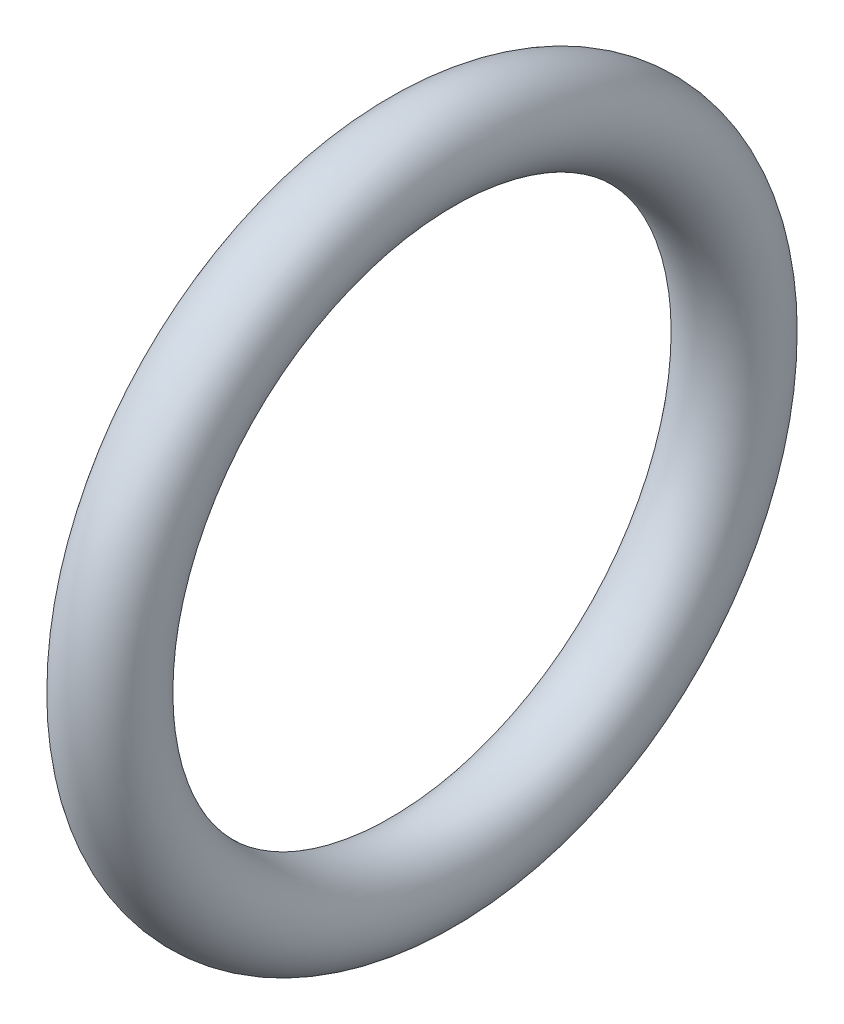
SolidWorks part; units mm, degrees
ref_plane "前视基准面" through (0, 0, 0) normal (0, 0, 1) x (1, 0, 0)
ref_plane "上视基准面" through (0, 0, 0) normal (0, 1, 0) x (1, 0, 0)
ref_plane "右视基准面" through (0, 0, 0) normal (1, 0, 0) x (0, 0, -1)
sketch "草图1" plane through (0, 0, 0) normal (0, 0, 1) x (1, 0, 0)
  line L0 (0, 0) -> (42.4841, 0) construction
  circle A0 centre (0, 3.5) radius 0.5
  circle A1 centre (0, -3.5) radius 0.5 construction
  dimension "D1" = 6
  dimension "D2" = 8
revolve "旋转1" add sketch "草图1" angle 360 about L0
ref_plane "基准面1" through (0, 0, 0) normal (1, 0, 0) x (0, 0, -1)
